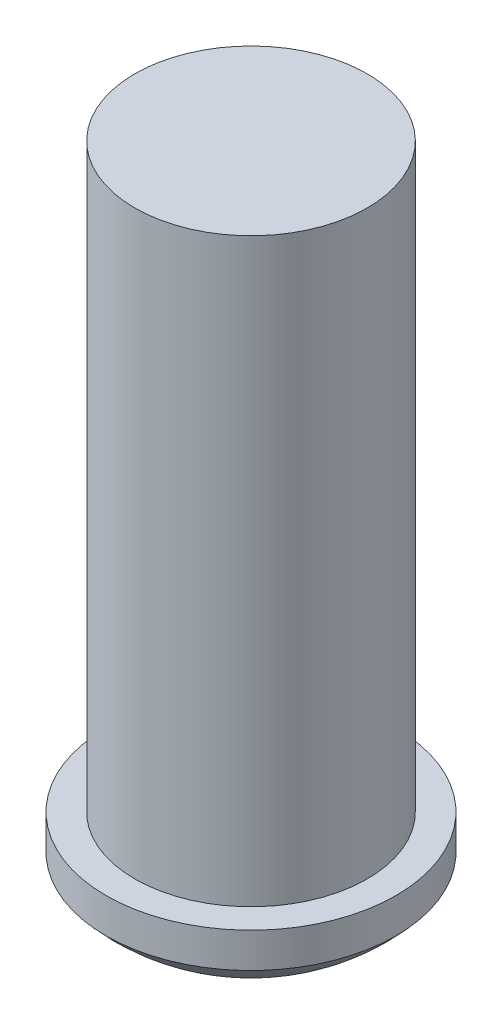
SolidWorks part; units mm, degrees
material "E-玻璃纤维"
ref_plane "前视基准面" through (0, 0, 0) normal (0, 0, 1) x (1, 0, 0)
ref_plane "上视基准面" through (0, 0, 0) normal (0, 1, 0) x (1, 0, 0)
ref_plane "右视基准面" through (0, 0, 0) normal (1, 0, 0) x (0, 0, -1)
sketch "草图1" plane through (0, 0, 0) normal (0, 1, 0) x (1, 0, 0)
  circle A0 centre (0, 0) radius 1
extrude "凸台-拉伸1" add sketch "草图1" along normal blind 5
sketch "草图5" plane through (0, 0, 0) normal (0, 0, 1) x (1, 0, 0)
  line L0 (0, 0) -> (0, -0.8037)
  line L1 (-1, 0) -> (1, 0) construction
  line L2 (0, 0) -> (-1.2472, 0)
  line L3 (-1.2472, 0) -> (-1.2472, -0.3004)
  spline S0 degree 2 poles (0, -0.8037) (-0.7593, -0.8569) (-1.2472, -0.3004) knots 0 0 0 1 1 1
revolve "旋转1" add sketch "草图5" angle 360 about L0
